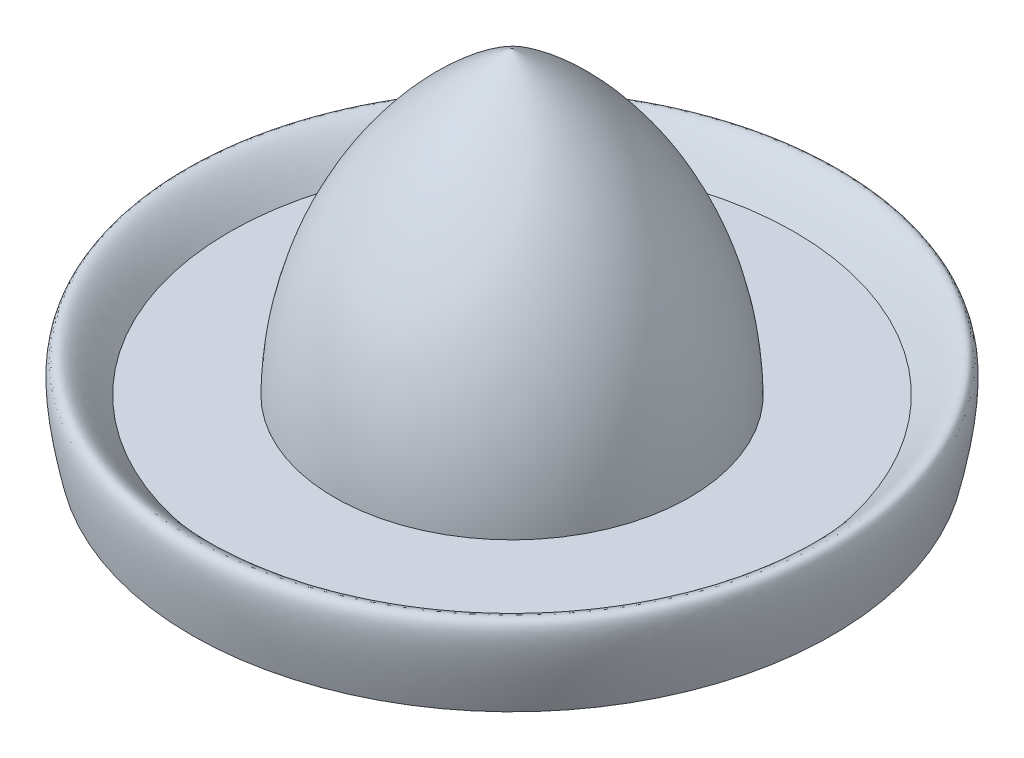
SolidWorks part; units mm, degrees
ref_plane "Front Plane" through (0, 0, 0) normal (0, 0, 1) x (1, 0, 0)
ref_plane "Top Plane" through (0, 0, 0) normal (0, 1, 0) x (1, 0, 0)
ref_plane "Right Plane" through (0, 0, 0) normal (1, 0, 0) x (0, 0, -1)
sketch "Sketch1" plane through (0, 0, 0) normal (1, 0, 0) x (0, 0, -1)
  line L0 (12.6745, 0) -> (15.361, 0)
  line L1 (15.361, 0) -> (27.7002, 0)
  line L2 (15.361, 4.155) -> (24.4266, 4.155)
  line L3 (0, 30.0925) -> (0, 27.5743)
  arc A0 (15.361, 4.155) -> (0, 30.0925) centre (-14.9282, 3.7342) ccw
  arc A1 (0, 27.5743) -> (12.6745, 0) centre (-18.9944, 2.1435) cw
  spline S0 degree 2 poles (27.7002, 0) (30.337, 11.8384) (24.4266, 4.155) knots 0 0 0 1 1 1
  point P3 (0, 0)
ref_axis "Axis1" through (0, 0, 0) along (0, 1, 0)
revolve "Revolve1" add sketch "Sketch1" angle 360 about axis through (0, 0, 0) along (0, 1, 0)
